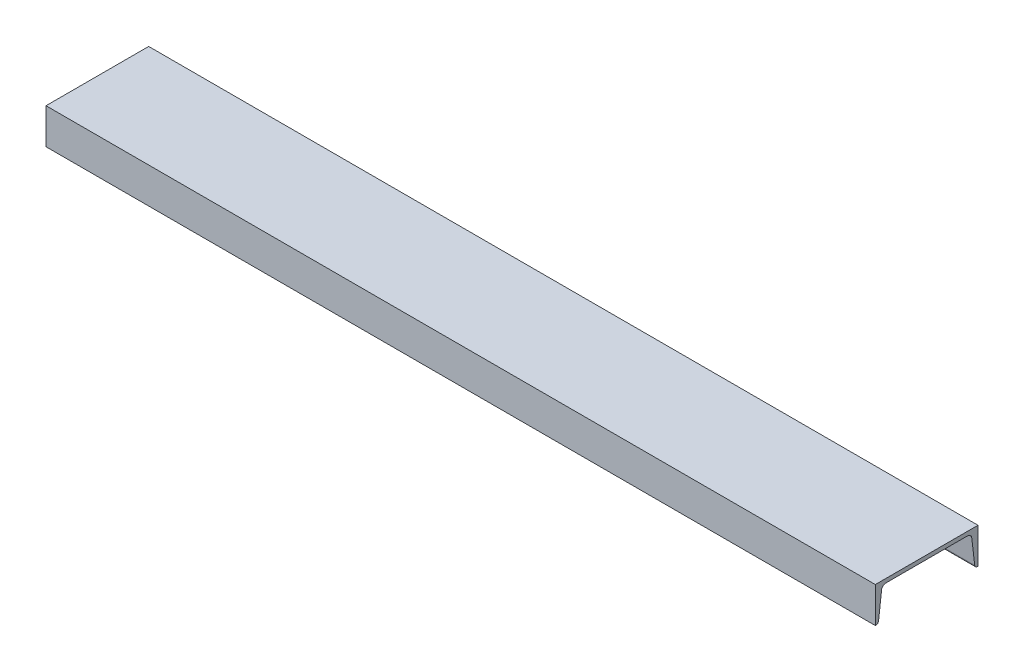
SolidWorks part; units mm, degrees
ref_plane "Спереди" through (0, 0, 0) normal (0, 0, 1) x (1, 0, 0)
ref_plane "Сверху" through (0, 0, 0) normal (0, 1, 0) x (1, 0, 0)
ref_plane "Справа" through (0, 0, 0) normal (1, 0, 0) x (0, 0, -1)
sketch "Эскиз2" plane through (0, 0, 0) normal (1, 0, 0) x (0, 0, -1)
  line L0 (130, 0) -> (-130, 0)
  line L1 (-130, 0) -> (-130, -90)
  line L2 (0, 0) -> (0, -100) construction
  line L3 (101.8373, -10) -> (-101.8373, -10)
  line L4 (-113.796, -16.7206) -> (-121.7267, -83.8216)
  line L5 (-130, -90) -> (-128.6783, -90)
  line L6 (130, -90) -> (128.6783, -90)
  line L7 (113.796, -16.7206) -> (121.7267, -83.8216)
  line L8 (130, 0) -> (130, -90)
  arc A0 (-101.8373, -10) -> (-113.796, -16.7206) centre (-101.8373, -24) ccw
  arc A1 (-128.6783, -90) -> (-121.7267, -83.8216) centre (-128.6783, -83) ccw
  arc A2 (128.6783, -90) -> (121.7267, -83.8216) centre (128.6783, -83) cw
  arc A3 (101.8373, -10) -> (113.796, -16.7206) centre (101.8373, -24) cw
  point P19 (0, -10)
extrude "Бобышка-Вытянуть2" add sketch "Эскиз2" along normal blind 2100 contours L0 L1 L5 A1 L4 A0 L3 A3 L7 A2 L6 L8
